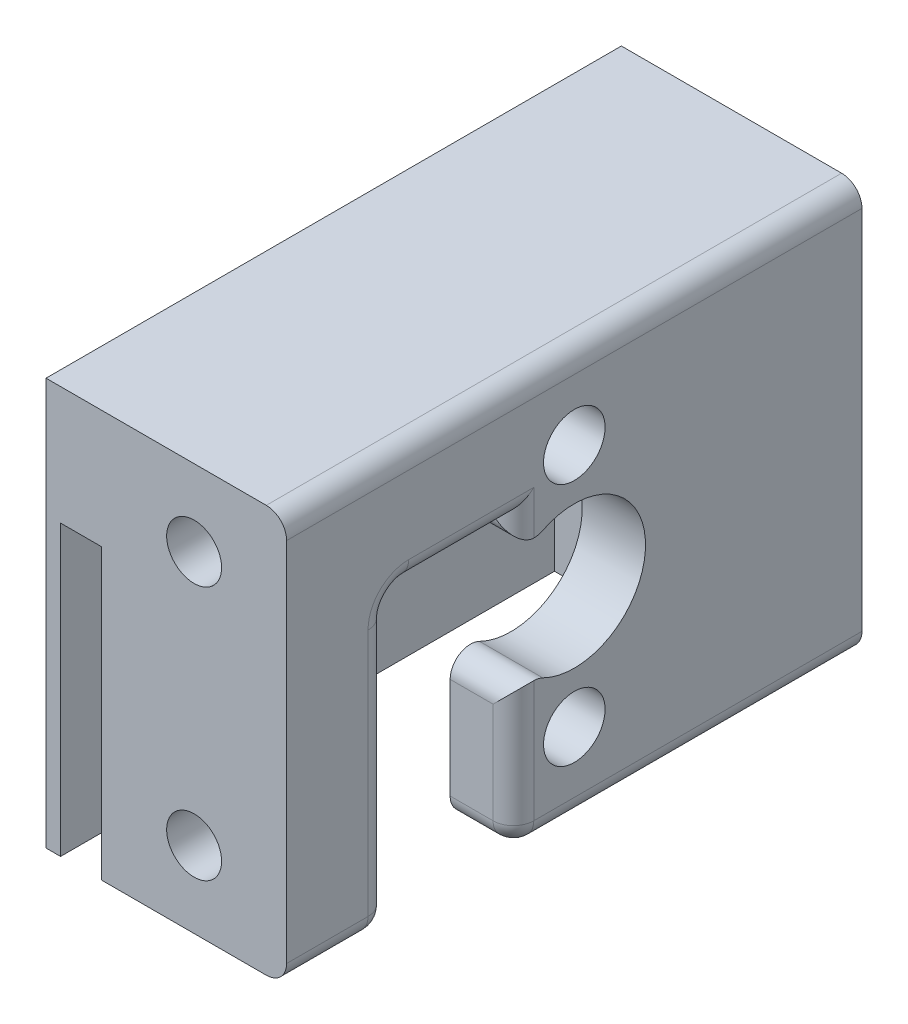
SolidWorks part; units mm, degrees
material "ABS"
ref_plane "X-Y Datum" through (0, 0, 0) normal (0, 0, 1) x (1, 0, 0)
ref_plane "X-Z Datum" through (0, 0, 0) normal (0, 1, 0) x (1, 0, 0)
ref_plane "Y-Z Datum" through (0, 0, 0) normal (1, 0, 0) x (0, 0, -1)
sketch "Sketch1" plane through (0, 0, 0) normal (0, 0, 1) x (1, 0, 0)
  line L1 (-11.825, 20) -> (11.825, 20)
  line L2 (-11.825, 20) -> (-11.825, -20)
  line L3 (-11.825, -20) -> (11.825, -20)
  line L4 (11.825, 20) -> (11.825, -20)
  line L5 (-11.825, 20) -> (11.825, -20) construction
  line L6 (-11.825, -20) -> (11.825, 20) construction
  point P0 (0, 0)
  dimension "D1" = 23.65
  dimension "D2" = 40
extrude "Boss-Extrude1" add sketch "Sketch1" along normal blind 56.55
sketch "Sketch2" plane through (0, 0, 56.55) normal (0, 0, 1) x (1, 0, 0)
  line L0 (-9.3955, -7.38) -> (-7.3635, -7.38) construction
  line L1 (-7.3635, -7.38) -> (-7.3635, 7.38) construction
  line L2 (-9.3955, 7.38) -> (-7.3635, 7.38) construction
  line L3 (-9.3955, 7.38) -> (-9.3955, -7.38) construction
  line L4 (-9.3955, -7.38) -> (-7.3635, -7.38)
  line L5 (-7.3635, -7.38) -> (-7.3635, 7.38)
  line L6 (-9.3955, 7.38) -> (-7.3635, 7.38)
  line L7 (-9.3955, 7.38) -> (-9.3955, -7.38)
  line L12 (-10.3955, -7.38) -> (-10.3955, -20)
  line L13 (-11.825, -20) -> (11.825, -20) construction
  line L14 (-7.3635, 8.38) -> (5.6045, 8.38)
  line L15 (5.6045, 8.38) -> (5.6045, -20)
  line L16 (-6.3635, -7.38) -> (-6.3635, 8.38) construction
  line L17 (-10.3955, 8.38) -> (-7.3635, 8.38)
  line L18 (-9.3955, 8.38) -> (-7.3635, 8.38) construction
  line L19 (-10.3955, 8.38) -> (-10.3955, -7.38)
  line L21 (-6.3635, -20) -> (-6.3635, 8.38)
  line L22 (-9.3955, 8.38) -> (-6.3635, 8.38) construction
  line L23 (-10.3955, 7.38) -> (-10.3955, -7.38) construction
  dimension "D2" = 16
  dimension "D1" = 1
  dimension "D3" = 1
  dimension "D4" = 1
extrude "Cut-Extrude1" cut sketch "Sketch2" against normal through all
sketch "Sketch3" plane through (11.825, 0, 0) normal (1, 0, 0) x (0, 0, -1)
  line L0 (-28.275, 20) -> (-28.275, -20) construction
  line L1 (-56.55, 20) -> (0, 20) construction
  line L2 (-56.55, -20) -> (0, -20) construction
  circle A0 centre (-28.275, 0) radius 7
  dimension "D1" = 14
extrude "Cut-Extrude2" cut sketch "Sketch3" against normal up to surface (6.2205 mm away) up to face at (5.6045, -5.81, 28.275)
sketch "Sketch6" plane through (11.825, 0, 0) normal (1, 0, 0) x (0, 0, -1)
  circle A0 centre (-28.275, -12) radius 2 construction
  circle A1 centre (-28.275, 12) radius 2 construction
  circle A2 centre (-28.275, -12) radius 2 construction
  circle A3 centre (-28.275, 12) radius 2 construction
  circle A4 centre (-28.275, 12) radius 3.025
  circle A5 centre (-28.275, -12) radius 3.025
  dimension "D1" = 6.05
extrude "Cut-Extrude4" cut sketch "Sketch6" against normal blind 8 contours A4 | A5
sketch "Sketch4" plane through (0, 8.38, 0) normal (0, -1, 0) x (1, 0, 0)
  line L0 (-7.3635, 61.468) -> (-7.3635, 34.29) construction
  line L1 (-7.3635, 61.468) -> (-7.3635, 34.29) construction
  line L2 (-7.3635, 46.55) -> (5.6045, 46.55)
  line L3 (-6.3635, 61.468) -> (-6.3635, 34.29)
  line L4 (5.6045, 56.55) -> (-10.3955, 56.55)
  line L5 (-10.3955, 56.55) -> (-10.3955, 0)
  line L6 (-10.3955, 0) -> (5.6045, 0)
  line L7 (5.6045, 0) -> (5.6045, 56.55)
  line L8 (5.6045, 56.55) -> (-10.3955, 56.55)
  line L9 (-10.3955, 56.55) -> (-10.3955, 0)
  line L10 (-10.3955, 0) -> (5.6045, 0)
  line L11 (5.6045, 0) -> (5.6045, 56.55)
  dimension "D2" = 10
  dimension "D1" = 0
  dimension "D3" = 1
extrude "Boss-Extrude2" add sketch "Sketch4" along normal up to surface (28.38 mm away) up to face at (8.7147, -20, 28.275)
sketch "Sketch5" plane through (11.825, 0, 0) normal (1, 0, 0) x (0, 0, -1)
  line L0 (-32.258, 4.84) -> (-32.258, -4.84) construction
  line L1 (-32.258, 20) -> (-32.258, -20) construction
  line L2 (-56.55, -20) -> (0, -20) construction
  line L3 (-56.55, 20) -> (0, 20) construction
  line L4 (-56.55, 0) -> (0, 0)
  line L5 (0, 8.38) -> (-46.55, 8.38) construction
  line L6 (-34.258, 20) -> (-34.258, -20)
  line L7 (-46.55, -20) -> (-46.55, 8.38) construction
  line L8 (-46.55, -20) -> (-46.55, 8.38)
  line L9 (0, -20) -> (0, 20)
  line L10 (0, 20) -> (-56.55, 20)
  line L11 (-56.55, 20) -> (-56.55, -20)
  line L12 (-56.55, -20) -> (0, -20)
  line L13 (0, -20) -> (0, 20)
  line L14 (0, 20) -> (-56.55, 20)
  line L15 (-56.55, 20) -> (-56.55, -20)
  line L16 (-56.55, -20) -> (0, -20)
  line L17 (0, 8.38) -> (-46.55, 8.38)
  point P15 (-32.258, 0)
  dimension "D1" = 0
  dimension "D2" = 2
extrude "Cut-Extrude3" cut sketch "Sketch5" against normal up to surface (6.2205 mm away)
fillet "Fillet5" radius 2 1 edges at (5.6045, 8.38, 17.129)
sketch "Sketch9" plane through (-10.3955, 0, 0) normal (1, 0, 0) x (0, 0, -1)
  line L1 (0, -20) -> (-8, -20)
  line L2 (0, -20) -> (0, -9)
  line L3 (0, -9) -> (-8, -9)
  line L4 (-8, -20) -> (-8, -9)
  dimension "D1" = 8
  dimension "D2" = 11
extrude "Boss-Extrude3" add sketch "Sketch9" along normal up to surface (16 mm away) up to face at (5.6045, -15.025, 28.275)
sketch "Sketch8" plane through (0, 0, 0) normal (0, 0, -1) x (-1, 0, 0)
  line L0 (0, 20) -> (0, 8.38) construction
  line L1 (-11.825, 20) -> (11.825, 20) construction
  line L2 (10.3955, 8.38) -> (-3.6045, 8.38) construction
  line L3 (-7.6296, 14.19) -> (7.6296, 14.19) construction
  line L4 (0, -20) -> (0, -9) construction
  line L5 (11.825, -20) -> (-11.825, -20) construction
  line L6 (-5.6045, -9) -> (10.3955, -9) construction
  line L7 (-4.1387, -14.5) -> (4.1387, -14.5) construction
  circle A0 centre (0, 14.19) radius 2.7
  circle A1 centre (0, -14.5) radius 2.7
  point P9 (0, 14.19)
  point P20 (0, -14.5)
  dimension "D1" = 5.4
extrude "Cut-Extrude6" cut sketch "Sketch8" against normal blind 6
sketch "Sketch7" plane through (0, 0, 56.55) normal (0, 0, 1) x (1, 0, 0)
  line L0 (2.7307, -20) -> (2.7307, 20) construction
  line L1 (-6.3635, -20) -> (11.825, -20) construction
  line L2 (11.825, 20) -> (-11.825, 20) construction
  line L3 (2.7307, 12.5) -> (2.7307, -12.5) construction
  circle A0 centre (2.7307, 12.5) radius 2.7
  circle A1 centre (2.7307, -12.5) radius 2.7
  point P11 (2.7307, 0)
  dimension "D1" = 5.4
  dimension "D2" = 25
extrude "Cut-Extrude5" cut sketch "Sketch7" against normal blind 8
fillet "Fillet4" radius 2 14 edges at (11.825, -11.8168, 34.258) (11.825, -20, 17.129) (8.7147, -3.6337, 34.258) (8.7147, 3.6337, 34.258) (11.825, -5.81, 46.55) (11.825, 6.0068, 34.258) (11.825, 8.38, 40.404) (11.825, 20, 28.275) (2.7308, -20, 46.55) (2.7308, 8.38, 46.55) (8.7147, -20, 34.258) (11.825, -20, 51.55) (5.6045, -14.5, 8) (5.6045, -9, 4)
sketch "Sketch10" [suppressed] plane through (0, 8.38, 0) normal (0, -1, 0) x (1, 0, 0)
  line L0 (-7.3635, 22.86) -> (-7.3635, -4.318) construction
  line L1 (-7.3635, 22.86) -> (-7.3635, -4.318) construction
  line L2 (-6.3635, 22.86) -> (-6.3635, -4.318)
  line L3 (5.6045, 0) -> (5.6045, 56.55) construction
  line L4 (5.6045, 0) -> (5.6045, 56.55)
  line L5 (5.6045, 10) -> (-6.3635, 10)
  line L6 (-10.3955, 0) -> (5.6045, 0) construction
  dimension "D2" = 10
  dimension "D1" = 1
extrude "Boss-Extrude4" [suppressed] add sketch "Sketch10" along normal up to surface (28.38 mm away)
sketch "Sketch11" [suppressed] plane through (11.825, 0, 0) normal (1, 0, 0) x (0, 0, -1)
  line L1 (-22.892, 8.38) -> (-22.892, -20)
  line L2 (-24.892, 4.84) -> (-24.892, -4.84) construction
  line L3 (-24.892, 4.84) -> (-24.892, -4.84) construction
  line L4 (-22.892, 4.84) -> (-22.892, -4.84) construction
  line L5 (-56.55, -20) -> (0, -20) construction
  line L6 (-10, -20) -> (-10, 8.38) construction
  line L7 (-10, -20) -> (-10, 8.38)
  line L8 (-10, 8.38) -> (-56.55, 8.38) construction
  line L9 (-10, 8.38) -> (-56.55, 8.38)
  dimension "D1" = 2
extrude "Cut-Extrude7" [suppressed] cut sketch "Sketch11" against normal up to surface (6.2205 mm away)
fillet "Fillet6" [suppressed] radius 2
sketch "Sketch12" [suppressed] plane through (-10.3955, 0, 0) normal (1, 0, 0) x (0, 0, -1)
  line L1 (-56.55, -20) -> (-48.55, -20)
  line L2 (-56.55, -20) -> (-56.55, -9)
  line L3 (-56.55, -9) -> (-48.55, -9)
  line L4 (-48.55, -20) -> (-48.55, -9)
  dimension "D1" = 8
  dimension "D2" = 11
extrude "Boss-Extrude5" [suppressed] add sketch "Sketch12" along normal up to surface (16 mm away)
sketch "Sketch13" [suppressed] plane through (0, 0, 0) normal (0, 0, -1) x (-1, 0, 0)
  circle A0 centre (-2.7308, -12.038) radius 2.7
  circle A1 centre (-2.7308, 12.962) radius 2.7
  point P0 (-2.7308, -12.038)
  point P1 (-2.7308, 12.962)
  dimension "D1" = 5.4
extrude "Cut-Extrude8" [suppressed] cut sketch "Sketch13" against normal blind 8
sketch "Sketch14" [suppressed] plane through (0, 0, 56.55) normal (0, 0, 1) x (1, 0, 0)
  circle A0 centre (0, -14.038) radius 2.7
  circle A1 centre (0, 14.652) radius 2.7
  point P0 (0, -14.038)
  point P1 (0, 14.652)
  dimension "D1" = 5.4
extrude "Cut-Extrude9" [suppressed] cut sketch "Sketch14" against normal blind 6
fillet "Fillet7" [suppressed] radius 2
